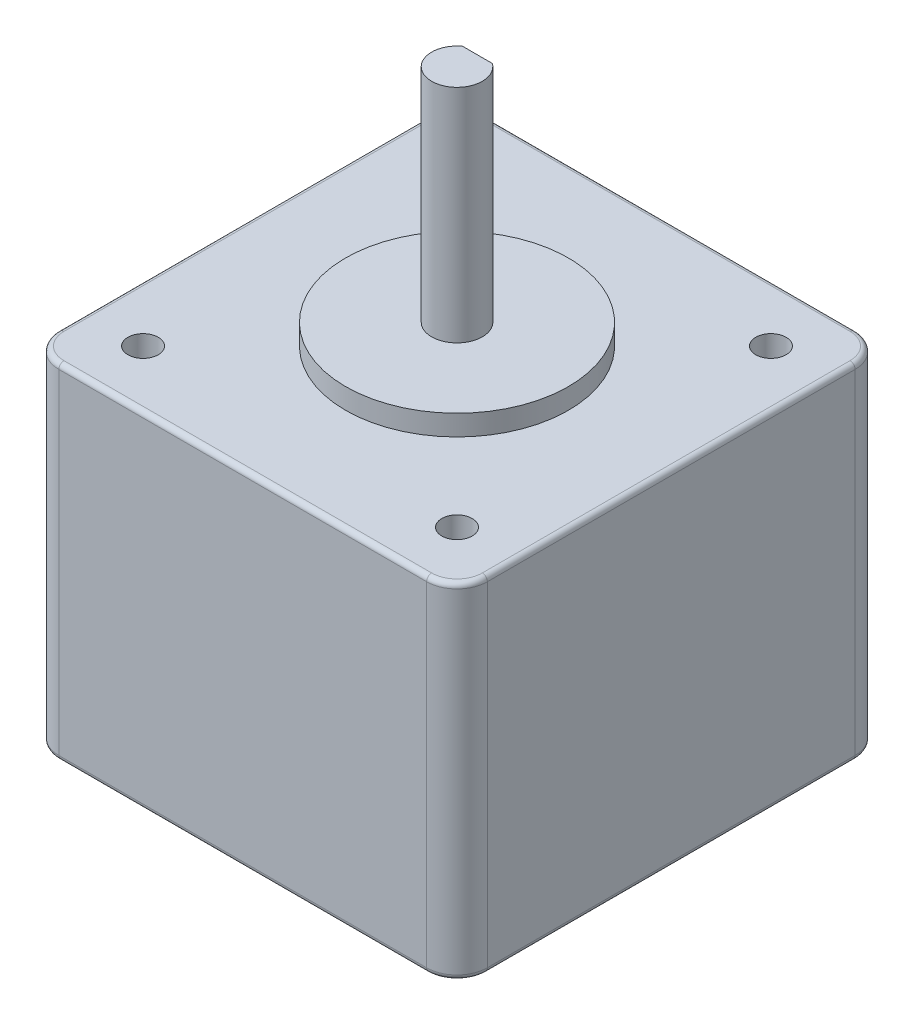
SolidWorks part; units mm, degrees
ref_plane "Front Plane" through (0, 0, 0) normal (0, 0, 1) x (1, 0, 0)
ref_plane "Top Plane" through (0, 0, 0) normal (0, 1, 0) x (1, 0, 0)
ref_plane "Right Plane" through (0, 0, 0) normal (1, 0, 0) x (0, 0, -1)
sketch "Sketch2" plane through (0, 0, 0) normal (0, 1, 0) x (1, 0, 0)
  line L0 (0, 42.3) -> (5.655, 36.645) construction
  line L1 (0, 0) -> (42.3, 0)
  line L2 (0, 0) -> (0, 42.3)
  line L3 (0, 42.3) -> (42.3, 42.3)
  line L4 (42.3, 0) -> (42.3, 42.3)
  line L5 (5.655, 36.645) -> (36.645, 36.645) construction
  line L6 (5.655, 36.645) -> (5.655, 5.655) construction
  line L7 (5.655, 5.655) -> (36.645, 5.655) construction
  line L8 (36.645, 36.645) -> (36.645, 5.655) construction
  line L9 (36.645, 5.655) -> (42.3, 0) construction
  line L10 (36.645, 36.645) -> (42.3, 42.3) construction
  line L11 (0, 0) -> (5.655, 5.655) construction
  circle A0 centre (5.655, 36.645) radius 1.5
  circle A1 centre (36.645, 36.645) radius 1.5
  circle A2 centre (36.645, 5.655) radius 1.5
  circle A3 centre (5.655, 5.655) radius 1.5
  dimension "D3" = 3
  dimension "D1" = 42.3
  dimension "D2" = 30.99
extrude "Boss-Extrude1" add sketch "Sketch2" along normal blind 34
sketch "Sketch3" plane through (0, 34, 0) normal (0, 1, 0) x (1, 0, 0)
  line L0 (0, 42.3) -> (42.3, 0) construction
  circle A0 centre (21.15, 21.15) radius 11
  dimension "D1" = 22
extrude "Boss-Extrude2" add sketch "Sketch3" along normal blind 2.03
sketch "Sketch4" plane through (0, 36.03, 0) normal (0, 1, 0) x (1, 0, 0)
  circle A0 centre (21.15, 21.15) radius 2.5
  circle A1 centre (21.15, 21.15) radius 11 construction
  dimension "D1" = 5
extrude "Boss-Extrude3" add sketch "Sketch4" along normal blind 21.85
sketch "Sketch5" plane through (0, 57.88, 0) normal (0, 1, 0) x (1, 0, 0)
  line L0 (19.677, 23.17) -> (22.623, 23.17)
  circle A0 centre (21.15, 21.15) radius 2.5 construction
  arc A1 (19.677, 23.17) -> (22.623, 23.17) centre (21.15, 21.15) cw
  dimension "D1" = 4.52
extrude "Cut-Extrude1" cut sketch "Sketch5" against normal blind 14.86
fillet "Fillet1" radius 3 4 edges at (0, 17, -42.3) (42.3, 17, -42.3) (42.3, 17, 0) (0, 17, 0)
fillet "Fillet2" radius 0.5 16 edges at (0.8787, 0, -0.8787) (0, 0, -21.15) (0.8787, 0, -41.4213) (21.15, 0, -42.3) (41.4213, 0, -41.4213) (42.3, 0, -21.15) (41.4213, 0, -0.8787) (0.8787, 34, -0.8787) (0, 34, -21.15) (0.8787, 34, -41.4213) (21.15, 34, -42.3) (41.4213, 34, -41.4213) (42.3, 34, -21.15) (41.4213, 34, -0.8787) (21.15, 0, 0) (21.15, 34, 0)
ref_plane "Plane1" through (0, 0, -21.15) normal (0, 0, 1) x (1, 0, 0)
ref_plane "Plane2" through (21.15, 0, 0) normal (-1, 0, 0) x (0, 0, 1)
